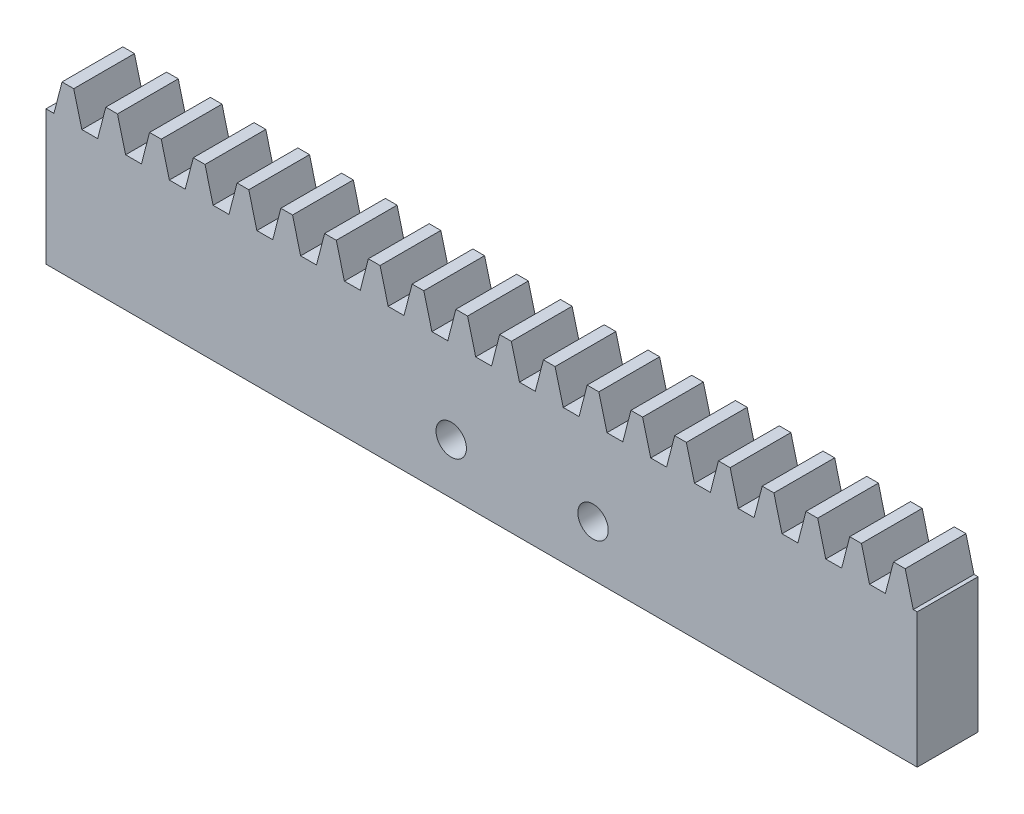
SolidWorks part; units mm, degrees
extrude "Blank" add sketch "BlankSke" against normal blind 6
sketch "BlankSke" plane through (0, 0, 0) normal (0, 0, 1) x (1, 0, 0)
  line L1 (0, 0) -> (86, 0)
  line L2 (0, 0) -> (0, 16.375)
  line L3 (0, 16.375) -> (86, 16.375)
  line L4 (86, 0) -> (86, 16.375)
  dimension "Length" = 86
  dimension "Blank_height" = 16.375
ref_plane "Plane1" through (0, 0, 0) normal (0, 0, 1) x (1, 0, 0)
ref_plane "Plane2" through (0, 0, 0) normal (0, 1, 0) x (1, 0, 0)
ref_plane "Plane3" through (0, 0, 0) normal (1, 0, 0) x (0, 0, -1)
sketch "HoldingSke" plane through (0, 0, 0) normal (0, 1, 0) x (1, 0, 0)
  line L0 (0, 0) -> (0.1012, 0.7202)
  line L1 (-15, 0) -> (100, 0) construction
  line L2 (0, 0) -> (-2.1039, 2.3779)
  line L3 (0, 0) -> (-11.863, 4.5341)
  line L4 (0, 0) -> (8.0624, 3.0949)
  line L5 (0, 0) -> (-23.7986, -8.8762)
  line L6 (0, 0) -> (-10.5278, -7.1032)
  line L9 (-67.7845, 28.3722) -> (15.4762, 49.9049)
  line L10 (-76.2, 3.7529) -> (-61.2, 3.7529)
  line L11 (0, 0) -> (-6, 0)
  line L12 (-76.2, 101.6) -> (-76.151, 101.6)
  line L13 (24.9733, 27.94) -> (52.9518, 28.4284)
  line L14 (24.9733, 27.94) -> (24.9743, 27.94)
  line L15 (24.9733, 27.94) -> (100.4006, 29.5858)
  circle A0 centre (0, 0) radius 19.05
  circle A1 centre (0, 0) radius 7.5
  circle A2 centre (0, 0) radius 12.7
  dimension "MPH" = 15
  dimension "Diameter" = 38.1
  dimension "Num_teeth" = 21
  dimension "Pitch" = 0.7273
  dimension "Show_teeth" = 998
  dimension "Thickness" = 12.7
  dimension "Ap" = 14.5
  dimension "Pitch_height" = 15
  dimension "Width" = 6
  dimension "Backlash" = 0.049
  dimension "Addendum_fac" = 1
  dimension "Dedendum_fac" = 1.25
  dimension "Clearance_fac" = 0.25
  dimension "Dedendum_add" = 0.001
  dimension "Length" = 86
  dimension "Module" = 1.375
sketch "TooCutSkeIll" plane through (0, 0, 0) normal (0, 0, 1) x (1, 0, 0)
  line L0 (-1.5719, 16.3338) -> (-0.8493, 13.5397)
  line L1 (-0.5155, 13.2812) -> (0.5155, 13.2812)
  line L2 (0.8493, 13.5397) -> (1.5719, 16.3338)
  line L3 (86, 16.375) -> (0, 16.375) construction
  line L4 (0, 0) -> (0, 64.897) construction
  line L5 (-13.208, 15) -> (12.954, 15) construction
  line L6 (0, 0) -> (86, 0) construction
  line L7 (1.2269, 15) -> (1.2269, 48.7463) construction
  line L8 (-1.2269, 15) -> (-1.2269, 48.7463) construction
  line L9 (1.6251, 16.375) -> (1.6251, 16.4004)
  line L10 (-1.6251, 16.375) -> (-1.6251, 16.4004)
  line L11 (-1.6251, 16.4004) -> (1.6251, 16.4004)
  arc A0 (0.5155, 13.2812) -> (0.8493, 13.5397) centre (0.5155, 13.626) ccw
  arc A1 (-0.8493, 13.5397) -> (-0.5155, 13.2812) centre (-0.5155, 13.626) ccw
  arc A2 (1.6251, 16.375) -> (1.5719, 16.3338) centre (1.6251, 16.32) ccw
  arc A3 (-1.5719, 16.3338) -> (-1.6251, 16.375) centre (-1.6251, 16.32) ccw
  dimension "Pitch_height" = 15
  dimension "Addendum_plus" = 1.4004
  dimension "Pressure_angle" = 14.5
  dimension "Gap_width" = 2.4538
  dimension "Dedendum" = 1.7188
extrude "ToothCutIll" [suppressed] cut sketch "TooCutSkeIll" against normal through all
sketch "TooCutSkeSim" plane through (0, 0, 0) normal (0, 0, 1) x (1, 0, 0)
  line L0 (0.7824, 13.2812) -> (-0.7824, 13.2812)
  line L1 (1.5891, 16.4004) -> (0.7824, 13.2812)
  line L2 (0, 17.4625) -> (0, 53.467) construction
  line L3 (1.5891, 16.4004) -> (-1.5891, 16.4004)
  line L6 (-1.5891, 16.4004) -> (-0.7824, 13.2812)
  line L9 (-1.2269, 15) -> (1.2269, 15) construction
  line L10 (0, 0) -> (86, 0) construction
  line L11 (1.2269, 15) -> (1.2269, 53.467) construction
  line L12 (-1.2269, 15) -> (-1.2269, 53.467) construction
  dimension "Pitch_height" = 15
  dimension "Addendum_plus" = 1.4004
  dimension "Pressure_angle" = 14.5
  dimension "Gap_width" = 2.4538
  dimension "Dedendum" = 1.7188
extrude "ToothCutSim" cut sketch "TooCutSkeSim" against normal through all
pattern_linear "TeethCuts" count 21 spacing 4.3197 along (1, 0, 0) of "ToothCutIll", "ToothCutSim"
sketch "Esquisse1" plane through (0, 0, 0) normal (0, 0, 1) x (1, 0, 0)
  line L0 (0, 0) -> (86, 0) construction
  line L1 (0, 13.2812) -> (0, 0) construction
  circle A0 centre (40, 5) radius 1.5
  circle A1 centre (54, 5) radius 1.5
  dimension "D1" = 3
  dimension "D2" = 3
  dimension "D3" = 14
  dimension "D4" = 5
  dimension "D5" = 40
extrude "Enlèv. mat.-Extru.1" cut sketch "Esquisse1" against normal through all
equation "' \"Module@HoldingSke\" = 6.35"
equation "' \"Num_teeth@HoldingSke\" = 12"
equation "' \"Ap@HoldingSke\" =  20"
equation "' \"Ap@HoldingSke\" = 20"
equation "' \"Width@HoldingSke\" = 0.25 * 25.4"
equation "' \"Show_teeth@HoldingSke\" = 500"
equation "' \"Backlash@HoldingSke\" = 0.009 * 25.4"
equation "' \"Addendum_fac@HoldingSke\" = 1.0"
equation "' \"Dedendum_fac@HoldingSke\" = 1.25"
equation "' \"Dedendum_add@HoldingSke\" = 0.00005 * 25.4"
equation "' \"Clearance_fac@HoldingSke\" = 0.25"
equation "' \"Pitch_height@HoldingSke\" = 1 * 25.4"
equation "' \"Length@HoldingSke\" = 4.71 * 25.4"
equation "\"Pitch@HoldingSke\" = 1 / \"Module@HoldingSke\""
equation "\"MPH@HoldingSke\" = \"Dedendum_fac@HoldingSke\" / \"Pitch@HoldingSke\" + 2 * \"Dedendum_add@HoldingSke\" + 0.002 * 25.4"
equation "\"MPH@HoldingSke\" = ((sgn( \"MPH@HoldingSke\" - \"Pitch_height@HoldingSke\")+1)*( \"MPH@HoldingSke\" - \"Pitch_height@HoldingSke\"))/2 + \"Pitch_height@HoldingSke\""
equation "\"Blank_height@BlankSke\" = \"Pitch_height@HoldingSke\" + \"Addendum_fac@HoldingSke\"  / \"Pitch@HoldingSke\" "
equation "\"Length@BlankSke\" =  \"Length@HoldingSke\""
equation "\"Face_width@Blank\" = \"Width@HoldingSke\""
equation "\"Pressure_angle@TooCutSkeIll\" = \"Ap@HoldingSke\""
equation "\"Addendum_plus@TooCutSkeIll\" =  \"Addendum_fac@HoldingSke\"  / \"Pitch@HoldingSke\" + 0.001 *25.4"
equation "\"Dedendum@TooCutSkeIll\" = \"Dedendum_fac@HoldingSke\"  / \"Pitch@HoldingSke\""
equation "\"Pitch_height@TooCutSkeIll\" =  \"MPH@HoldingSke\""
equation "\"Gap_width@TooCutSkeIll\" = 3.14159265 / 2 / \"Pitch@HoldingSke\" + 6 * \"Backlash@HoldingSke\""
equation "\"Pressure_angle@TooCutSkeSim\" = \"Ap@HoldingSke\""
equation "\"Addendum_plus@TooCutSkeSim\" =  \"Addendum_fac@HoldingSke\"  / \"Pitch@HoldingSke\" + 0.001 * 25.4"
equation "\"Dedendum@TooCutSkeSim\" = \"Dedendum_fac@HoldingSke\"  / \"Pitch@HoldingSke\""
equation "\"Pitch_height@TooCutSkeSim\" =  \"MPH@HoldingSke\""
equation "\"Gap_width@TooCutSkeSim\" = 3.14159265 / 2 / \"Pitch@HoldingSke\" + 6 * \"Backlash@HoldingSke\""
equation "\"Root_fillet@TooCutSkeIll\" = \"Clearance_fac@HoldingSke\" / \"Pitch@HoldingSke\" + \"Dedendum_add@HoldingSke\""
equation "\"Break_rad@TooCutSkeIll\" = 0.02 / \"Pitch@HoldingSke\" * 2"
equation "\"Linear_pitch@TeethCuts\" = 3.14159265 / \"Pitch@HoldingSke\""
equation "\"Num_teeth@HoldingSke\" = int( ( \"Length@HoldingSke\" + 0 ) / (3.14159265 / \"Pitch@HoldingSke\")) + 0.9999  + 1"
equation " \"Num_teeth@TeethCuts\" = int( \"Show_teeth@HoldingSke\" ) + 1"
equation " \"Num_teeth@TeethCuts\" = ((sgn( \"Num_teeth@TeethCuts\" - \"Num_teeth@HoldingSke\" )-1)*( \"Num_teeth@TeethCuts\" - \"Num_teeth@HoldingSke\" ))/-2+ \"Num_teeth@HoldingSke\""
equation " \"Num_teeth@TeethCuts\" = ((sgn( \"Num_teeth@TeethCuts\" - 2.0)+1)*( \"Num_teeth@TeethCuts\" - 2.0))/2 +2.0"
